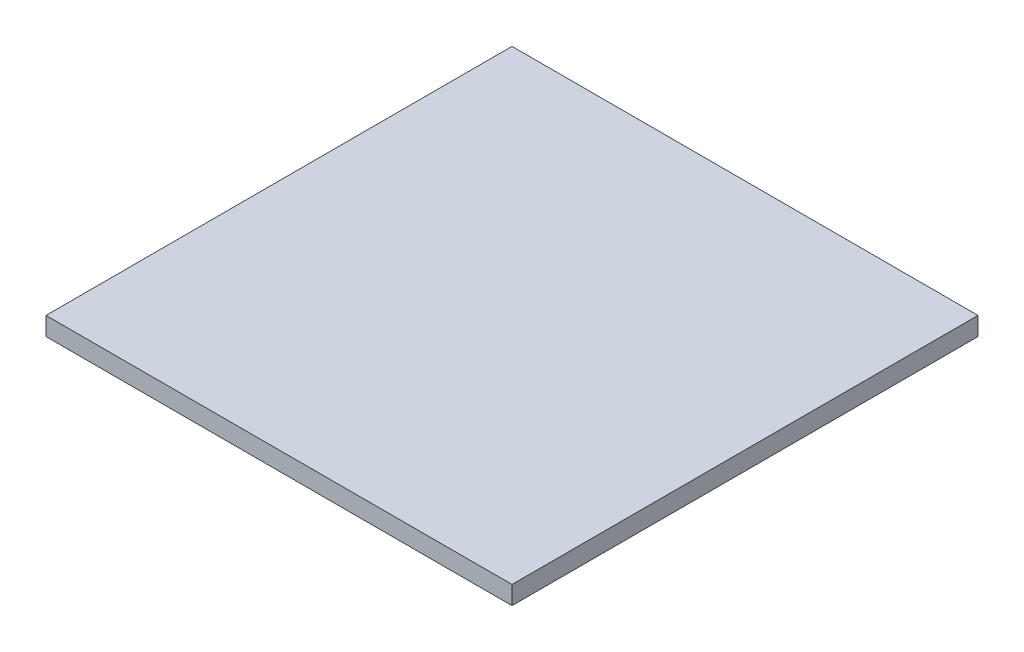
SolidWorks part; units mm, degrees
material "Maple"
ref_plane "Front Plane" through (0, 0, 0) normal (0, 0, 1) x (1, 0, 0)
ref_plane "Top Plane" through (0, 0, 0) normal (0, 1, 0) x (1, 0, 0)
ref_plane "Right Plane" through (0, 0, 0) normal (1, 0, 0) x (0, 0, -1)
sketch "Sketch1" plane through (0, 0, 0) normal (0, 1, 0) x (1, 0, 0)
  line L1 (-38.1, -38.1) -> (38.1, -38.1)
  line L2 (-38.1, -38.1) -> (-38.1, 38.1)
  line L3 (-38.1, 38.1) -> (38.1, 38.1)
  line L4 (38.1, -38.1) -> (38.1, 38.1)
  line L5 (-38.1, -38.1) -> (38.1, 38.1) construction
  line L6 (-38.1, 38.1) -> (38.1, -38.1) construction
  point P0 (0, 0)
  dimension "D1" = 76.2
extrude "Boss-Extrude1" add sketch "Sketch1" against normal blind 3
